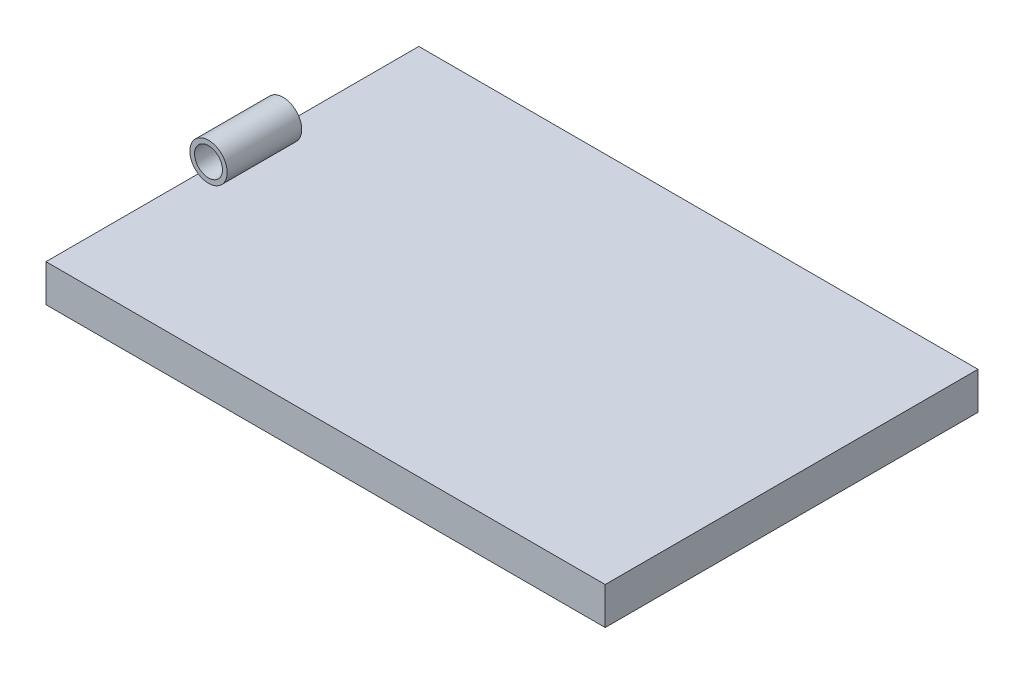
SolidWorks part; units mm, degrees
ref_plane "Front Plane" through (0, 0, 0) normal (0, 0, 1) x (1, 0, 0)
ref_plane "Top Plane" through (0, 0, 0) normal (0, 1, 0) x (1, 0, 0)
ref_plane "Right Plane" through (0, 0, 0) normal (1, 0, 0) x (0, 0, -1)
sketch "Sketch1" plane through (0, 0, 0) normal (0, 1, 0) x (1, 0, 0)
  line L1 (0, 0) -> (76.2, 0)
  line L2 (0, 0) -> (0, 50.8)
  line L3 (0, 50.8) -> (76.2, 50.8)
  line L4 (76.2, 0) -> (76.2, 50.8)
  dimension "D1" = 76.2
  dimension "D2" = 50.8
extrude "Boss-Extrude1" add sketch "Sketch1" along normal blind 5.08
ref_plane "Plane1" through (0, 0, -25.4) normal (0, 0, 1) x (1, 0, 0)
sketch "Sketch2" plane through (0, 0, -25.4) normal (0, 0, 1) x (1, 0, 0)
  line L0 (0, 5.08) -> (76.2, 5.08) construction
  line L1 (0, 5.08) -> (76.2, 5.08)
  circle A0 centre (1.8254, 7.62) radius 2.54
  circle A1 centre (1.8254, 7.62) radius 1.905
  dimension "D1" = 3.81
  dimension "D2" = 5.08
  dimension "D3" = 1.8254
extrude "Boss-Extrude2" add sketch "Sketch2" along normal blind 5.08 and the other way blind 5.08 separate body contours A0 | A1
